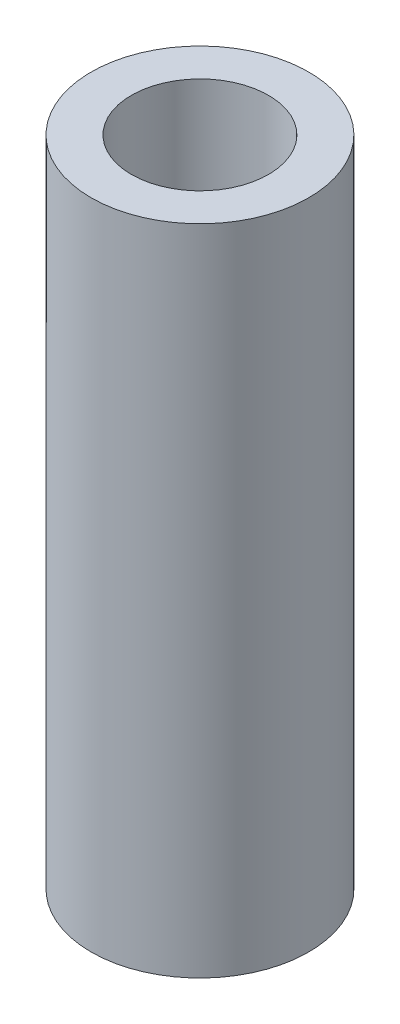
SolidWorks part; units mm, degrees
material "6061-T6 (SS)"
ref_plane "X-Y Datum" through (0, 0, 0) normal (0, 0, 1) x (1, 0, 0)
ref_plane "X-Z Datum" through (0, 0, 0) normal (0, 1, 0) x (1, 0, 0)
ref_plane "Y-Z Datum" through (0, 0, 0) normal (1, 0, 0) x (0, 0, -1)
sketch "Sketch1" plane through (0, 0, 0) normal (0, 1, 0) x (1, 0, 0)
  circle A0 centre (0, 0) radius 3.175
  circle A1 centre (0, 0) radius 2
  dimension "D1" = 6.35
  dimension "D2" = 4
extrude "Boss-Extrude1" add sketch "Sketch1" against normal blind 19.05
